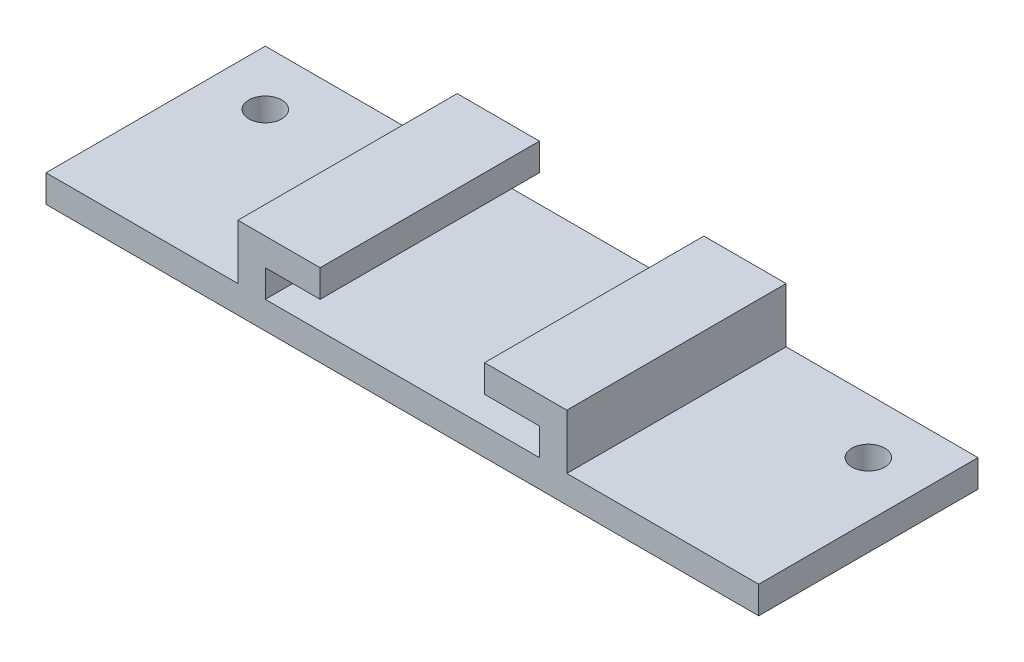
SolidWorks part; units mm, degrees
ref_plane "Front Plane" through (0, 0, 0) normal (0, 0, 1) x (1, 0, 0)
ref_plane "Top Plane" through (0, 0, 0) normal (0, 1, 0) x (1, 0, 0)
ref_plane "Right Plane" through (0, 0, 0) normal (1, 0, 0) x (0, 0, -1)
sketch "Sketch1" plane through (0, 0, 0) normal (0, 1, 0) x (1, 0, 0)
  line L1 (-130, -40) -> (130, -40)
  line L2 (-130, -40) -> (-130, 40)
  line L3 (-130, 40) -> (130, 40)
  line L4 (130, -40) -> (130, 40)
  line L5 (-130, -40) -> (130, 40) construction
  line L6 (-130, 40) -> (130, -40) construction
  point P0 (0, 0)
  dimension "D1" = 260
  dimension "D2" = 80
extrude "Boss-Extrude1" add sketch "Sketch1" along normal blind 10
sketch "Sketch2" plane through (0, 0, 40) normal (0, 0, 1) x (1, 0, 0)
  line L0 (-130, 5) -> (130, 5) construction
  line L1 (-130, 10) -> (-130, 0) construction
  line L2 (130, 10) -> (130, 0) construction
  line L3 (-30, 25) -> (-55, 25)
  line L4 (-55, 25) -> (-55, 5)
  line L5 (-55, 5) -> (55, 5)
  line L6 (55, 5) -> (55, 25)
  line L7 (55, 25) -> (30, 25)
  point P13 (0, 5)
  point P14 (0, 5)
  dimension "D1" = 110
  dimension "D2" = 20
  dimension "D3" = 25
extrude "Extrude-Thin2" add sketch "Sketch2" against normal up to surface (80 mm away) thin up to face at (0, 5, -40) thin type mid plane wall 10
hole_wizard "Ø1.0mm Dowel Hole1" positions "3DSketch1" profile "Sketch3" hole size "Ø1.0" standard "ANSI Metric" end condition through all
sketch3d "3DSketch1"
  line L0 (-60, 10, -40) -> (-130, 10, -40) construction
  line L1 (130, 10, -40) -> (60, 10, -40) construction
  line L2 (-130, 10, -40) -> (-130, 10, 40) construction
  point P8 (-95, 10, -40)
  point P12 (95, 10, -40)
  point P29 (110, 10, -20)
  point P31 (-110, 10, -20)
  point P41 (0, 0, 0)
  dimension "D1" = 220
  dimension "D2" = 20
  dimension "D3" = 20
sketch "Sketch3" plane through (-110, 10, -20) normal (1, 0, 0) x (0, 0, 1)
  line L0 (0, 0) -> (0, 10)
  line L1 (0, 10) -> (6, 10)
  line L2 (6, 10) -> (6, 0)
  line L5 (6, 0) -> (0, 0)
  line L11 (0, -6.35) -> (0, 107.95) construction
  dimension "Thru Hole Dia." = 12
  dimension "Thru Hole Depth" = 10
